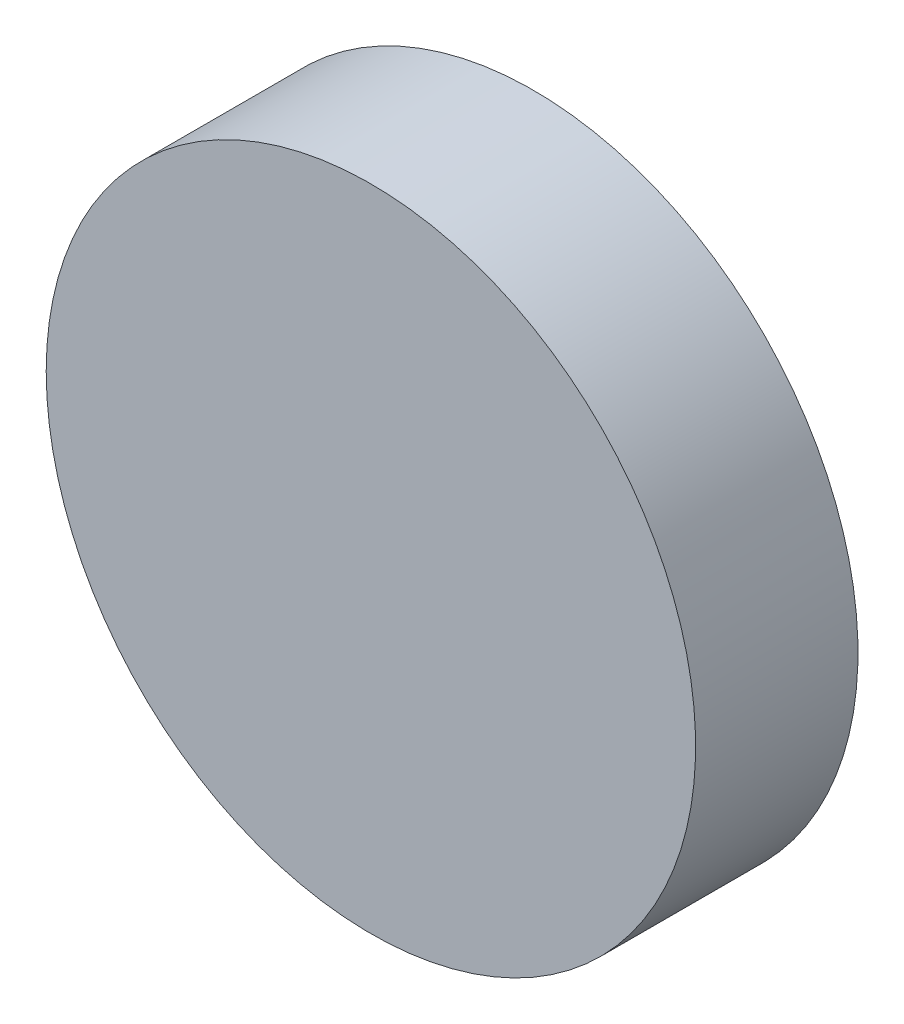
SolidWorks part; units mm, degrees
ref_plane "前视基准面" through (0, 0, 0) normal (0, 0, 1) x (1, 0, 0)
ref_plane "上视基准面" through (0, 0, 0) normal (0, 1, 0) x (1, 0, 0)
ref_plane "右视基准面" through (0, 0, 0) normal (1, 0, 0) x (0, 0, -1)
other "Configuration Table"
sketch "草图1" plane through (0, 0, 0) normal (0, 0, 1) x (1, 0, 0)
  circle A0 centre (0, 0) radius 52
  dimension "D1" = 104
extrude "凸台-拉伸1" add sketch "草图1" along normal blind 26
